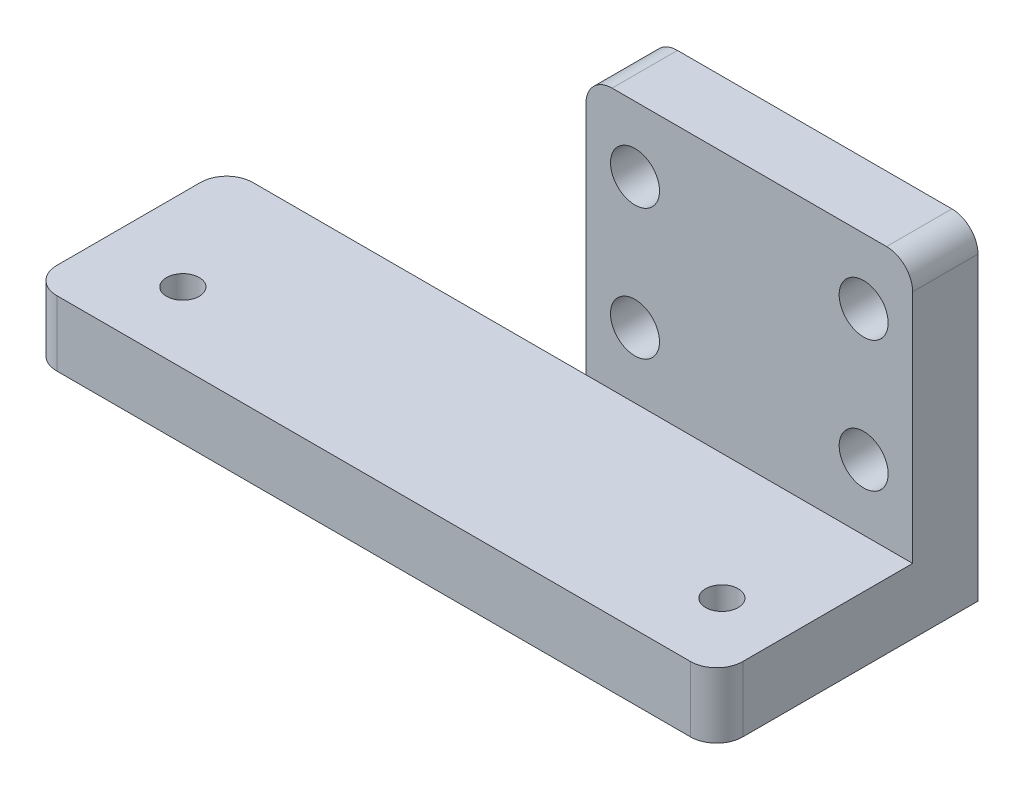
SolidWorks part; units mm, degrees
ref_plane "Front Plane" through (0, 0, 0) normal (0, 0, 1) x (1, 0, 0)
ref_plane "Top Plane" through (0, 0, 0) normal (0, 1, 0) x (1, 0, 0)
ref_plane "Right Plane" through (0, 0, 0) normal (1, 0, 0) x (0, 0, -1)
sketch "Sketch1" plane through (0, 0, 0) normal (0, 0, 1) x (1, 0, 0)
  line L1 (-15.875, -15.875) -> (15.875, -15.875)
  line L2 (-15.875, -15.875) -> (-15.875, 15.875)
  line L3 (-15.875, 15.875) -> (15.875, 15.875)
  line L4 (15.875, -15.875) -> (15.875, 15.875)
  line L5 (-15.875, -15.875) -> (15.875, 15.875) construction
  line L6 (-15.875, 15.875) -> (15.875, -15.875) construction
  circle A0 centre (-11.1125, -3.175) radius 2.3813
  circle A1 centre (-11.1125, 9.525) radius 2.3813
  circle A2 centre (11.1125, 9.525) radius 2.3813
  circle A3 centre (11.1125, -3.175) radius 2.3813
  point P0 (0, 0)
  dimension "D3" = 4.7625
  dimension "D4" = 4.7625
  dimension "D10" = 4.7625
  dimension "D11" = 4.7625
  dimension "D1" = 31.75
  dimension "D2" = 31.75
  dimension "D5" = 12.7
  dimension "D6" = 12.7
  dimension "D7" = 4.7625
  dimension "D8" = 12.7
  dimension "D9" = 12.7
  dimension "D12" = 4.7625
extrude "Boss-Extrude1" add sketch "Sketch1" along normal blind 6.35
sketch "Sketch2" plane through (0, 0, 6.35) normal (0, 0, 1) x (1, 0, 0)
  line L1 (-50.8, -15.875) -> (15.875, -15.875)
  line L2 (-50.8, -15.875) -> (-50.8, -9.525)
  line L3 (-50.8, -9.525) -> (15.875, -9.525)
  line L4 (15.875, -15.875) -> (15.875, -9.525)
  dimension "D1" = 66.675
  dimension "D2" = 6.35
extrude "Boss-Extrude2" add sketch "Sketch2" along normal blind 19.05
sketch "Sketch3" plane through (0, -9.525, 0) normal (0, 1, 0) x (1, 0, 0)
  line L0 (15.875, -25.4) -> (15.875, -6.35) construction
  line L1 (-15.875, -6.35) -> (-50.8, -6.35) construction
  circle A0 centre (9.525, -18.542) radius 1.5875
  circle A1 centre (-42.8625, -18.542) radius 1.5875
  dimension "D1" = 3.175
  dimension "D3" = 6.35
  dimension "D5" = 3.175
  dimension "D2" = 12.192
  dimension "D4" = 52.3875
extrude "Cut-Extrude1" cut sketch "Sketch3" against normal through all
fillet "Fillet1" radius 2.54 5 edges at (-15.875, 15.875, 3.175) (15.875, 15.875, 3.175) (15.875, -12.7, 25.4) (-50.8, -12.7, 6.35) (-50.8, -12.7, 25.4)
